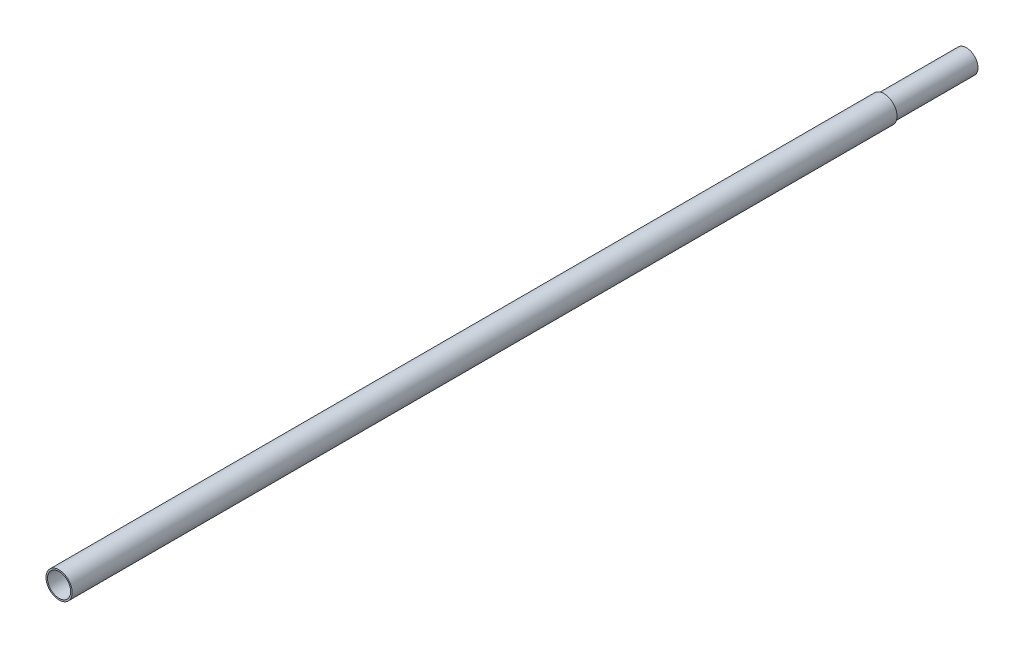
SolidWorks part; units mm, degrees
ref_plane "Front Plane" through (0, 0, 0) normal (0, 0, 1) x (1, 0, 0)
ref_plane "Top Plane" through (0, 0, 0) normal (0, 1, 0) x (1, 0, 0)
ref_plane "Right Plane" through (0, 0, 0) normal (1, 0, 0) x (0, 0, -1)
sketch "Sketch1" plane through (0, 0, 0) normal (0, 0, 1) x (1, 0, 0)
  circle A0 centre (0, 0) radius 11.227
  circle A1 centre (0, 0) radius 9.6395
extrude "Boss-Extrude1" add sketch "Sketch1" along normal blind 380
sketch "Sketch2" plane through (0, 0, 0) normal (0, 0, 1) x (1, 0, 0)
  circle A0 centre (0, 0) radius 12.7
  circle A1 centre (0, 0) radius 11.227
extrude "Boss-Extrude2" add sketch "Sketch2" along normal blind 800 from offset 80
